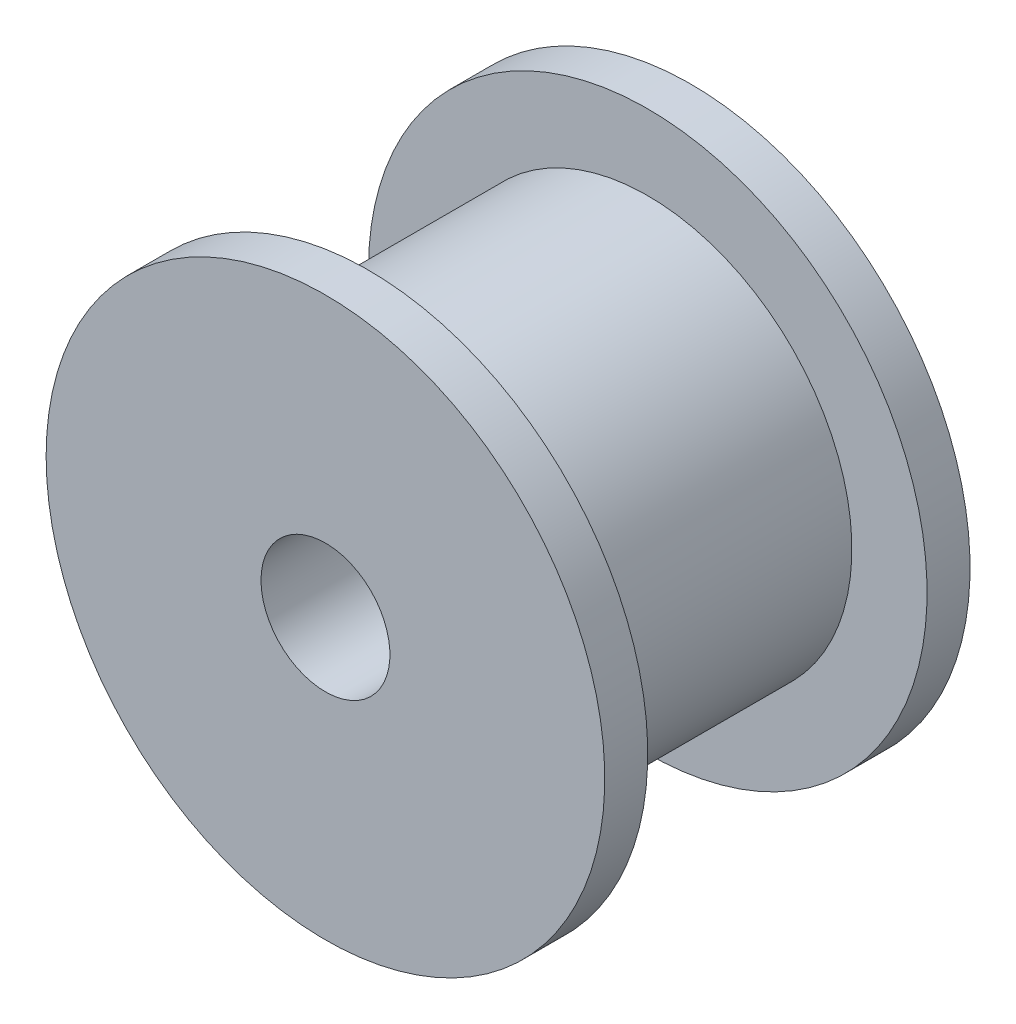
SolidWorks part; units mm, degrees
ref_plane "Front Plane" through (0, 0, 0) normal (1, 0, 0) x (0, 1, 0)
ref_plane "Top Plane" through (0, 0, 0) normal (0, 0, 1) x (0, 1, 0)
ref_plane "Right Plane" through (0, 0, 0) normal (0, 1, 0) x (-1, 0, 0)
sketch "Sketch2" plane through (0, 0, 0) normal (0, 1, 0) x (-1, 0, 0)
  line L1 (-6.5, 3.25) -> (-6.5, -3.25)
  line L2 (-6.5, -3.25) -> (-8.25, -3.25)
  line L3 (-8.25, -3.25) -> (-8.25, -4.25)
  line L4 (-8.25, -4.25) -> (-3.25, -4.25)
  line L5 (-3.25, -4.25) -> (-3.25, 4.25)
  line L6 (-3.25, 4.25) -> (-8.25, 4.25)
  line L7 (-8.25, 4.25) -> (-8.25, 3.25)
  line L8 (-8.25, 3.25) -> (-6.5, 3.25)
  line L9 (-8.25, -3.25) -> (-1.75, -3.25) construction
  line L10 (-1.75, -3.25) -> (-1.75, 0.5683) construction
  point P6 (-6.5, 0)
  dimension "D1" = 6.5
  dimension "D2" = 1
  dimension "D3" = 1
  dimension "D4" = 1.75
  dimension "D5" = 5
  dimension "D6" = 6.5
revolve "Revolve1" add sketch "Sketch2" angle 360 about L10
